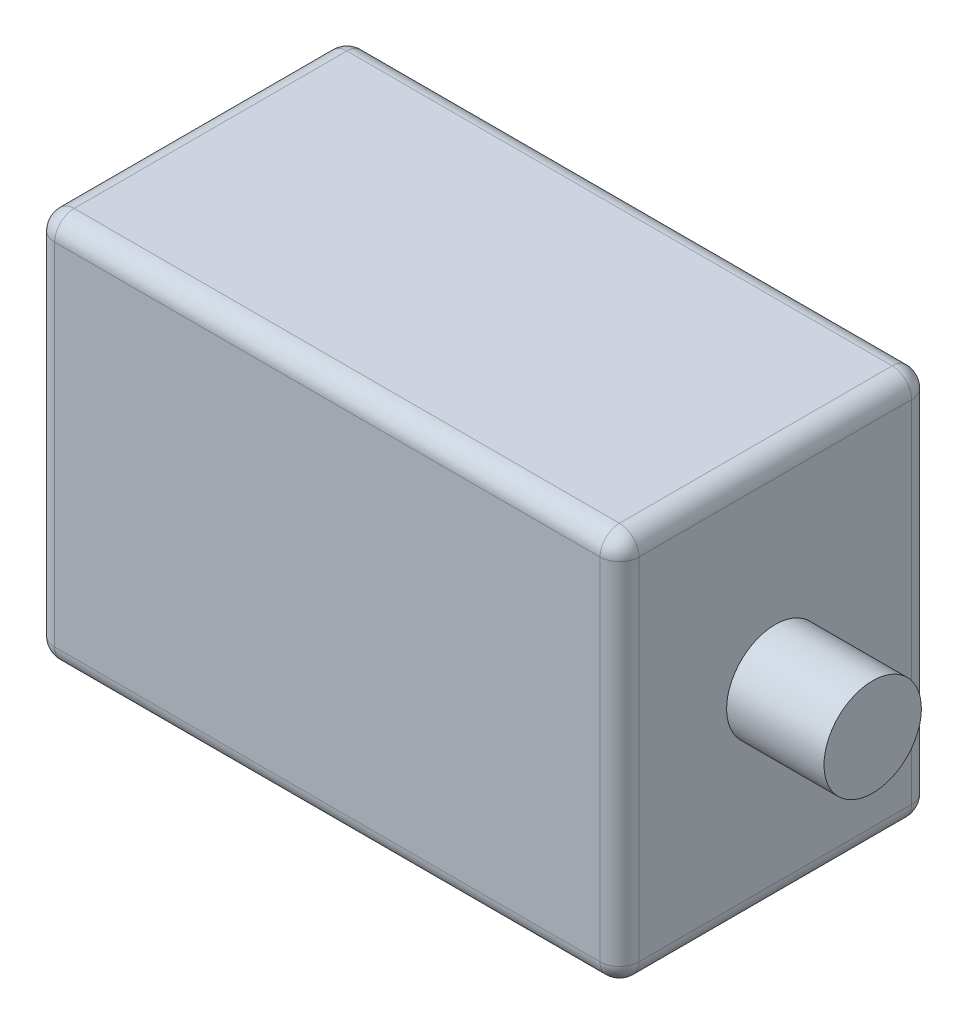
SolidWorks part; units mm, degrees
ref_plane "前视基准面" through (0, 0, 0) normal (0, 0, 1) x (1, 0, 0)
ref_plane "上视基准面" through (0, 0, 0) normal (0, 1, 0) x (1, 0, 0)
ref_plane "右视基准面" through (0, 0, 0) normal (1, 0, 0) x (0, 0, -1)
sketch "草图1" plane through (0, 0, 0) normal (0, 0, 1) x (1, 0, 0)
  line L1 (-15, 10) -> (15, 10)
  line L2 (-15, 10) -> (-15, -10)
  line L3 (-15, -10) -> (15, -10)
  line L4 (15, 10) -> (15, -10)
  line L5 (-15, 10) -> (15, -10) construction
  line L6 (-15, -10) -> (15, 10) construction
  point P0 (0, 0)
  dimension "D1" = 30
  dimension "D2" = 20
extrude "凸台-拉伸1" add sketch "草图1" along normal blind 16
sketch "草图2" plane through (15, 0, 0) normal (1, 0, 0) x (0, 0, -1)
  line L0 (-8, 10) -> (-8, -10) construction
  line L1 (-16, 10) -> (0, 10) construction
  line L2 (-16, -10) -> (0, -10) construction
  line L3 (-16, 0) -> (0, 0) construction
  line L4 (-16, -10) -> (-16, 10) construction
  circle A0 centre (-8, 0) radius 2.5
  dimension "D1" = 5
extrude "凸台-拉伸2" add sketch "草图2" along normal blind 5
fillet "圆角1" radius 1 12 edges at (-15, 0, 16) (-15, 10, 8) (-15, 0, 0) (-15, -10, 8) (0, -10, 0) (0, -10, 16) (0, 10, 16) (15, 0, 16) (15, 0, 0) (15, 10, 8) (0, 10, 0) (15, -10, 8)
